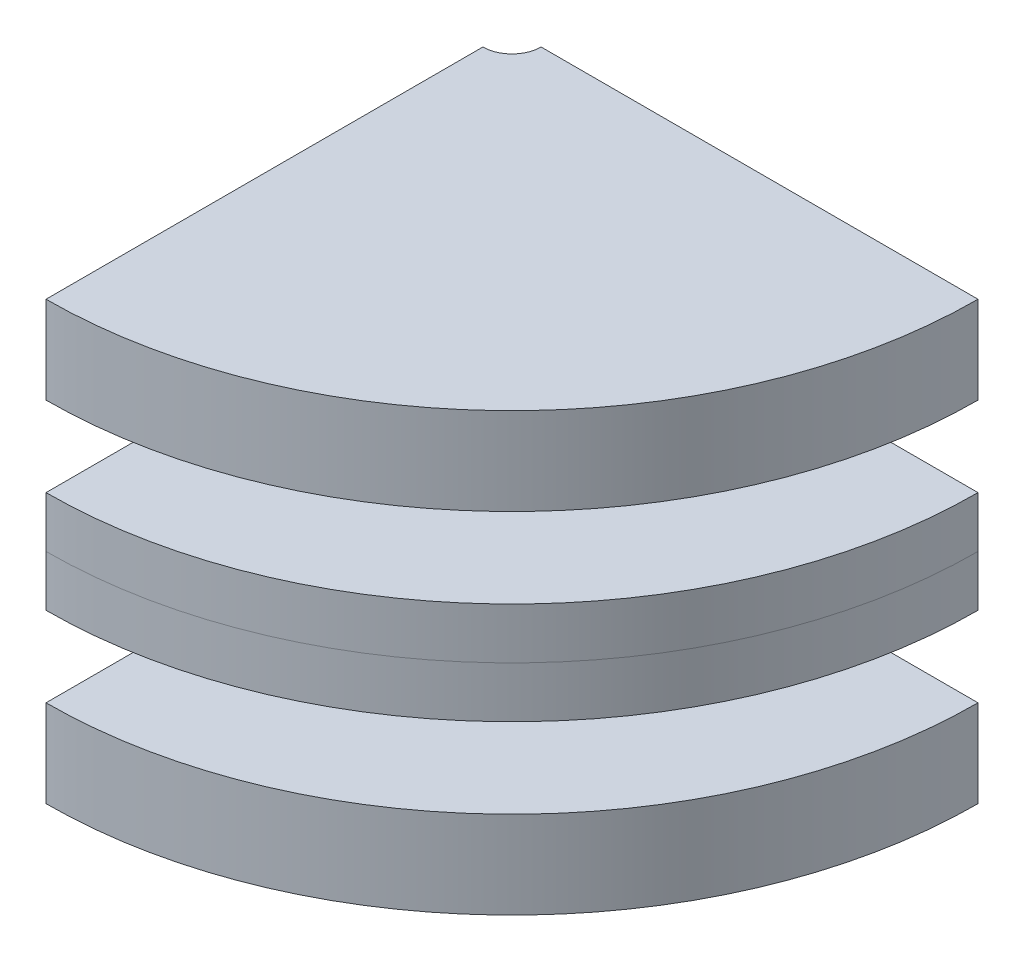
SolidWorks part; units mm, degrees
ref_plane "Front Plane" through (0, 0, 0) normal (0, 0, 1) x (1, 0, 0)
ref_plane "Top Plane" through (0, 0, 0) normal (0, 1, 0) x (1, 0, 0)
ref_plane "Right Plane" through (0, 0, 0) normal (1, 0, 0) x (0, 0, -1)
sketch "Sketch1" plane through (0, 0, 0) normal (0, 1, 0) x (1, 0, 0)
  line L0 (0, 0) -> (0, 15)
  line L1 (1, 16) -> (16, 16)
  line L2 (0, 0) -> (-15.7143, 0) construction
  line L3 (0, 15) -> (-10.8275, 15) construction
  arc A0 (0, 15) -> (1, 16) centre (0, 16) ccw
  arc A1 (0, 0) -> (16, 16) centre (0, 16) ccw
  point P5 (0, 7.5)
  point P6 (8.5, 16)
  point P9 (-10.8275, 15)
  dimension "D1" = 15
  dimension "D2" = 15
  dimension "D3" = 8.5
  dimension "D4" = 8.5
extrude "Boss-Extrude1" add sketch "Sketch1" along normal blind 3
ref_plane "Plane1" through (0, 5.75, 0) normal (0, 1, 0) x (1, 0, 0)
sketch "Sketch2" plane through (0, 5.75, 0) normal (0, 1, 0) x (1, 0, 0)
  line L0 (1, 16) -> (16, 16)
  line L1 (16, 16) -> (1, 16) construction
  line L2 (0, 15) -> (0, 0)
  arc A1 (0, 15) -> (1, 16) centre (0, 16) ccw
  arc A2 (0, 15) -> (1, 16) centre (0, 16) ccw construction
  arc A3 (0, 0) -> (16, 16) centre (0, 16) ccw
  arc A4 (0, 0) -> (16, 16) centre (0, 16) ccw construction
  point P13 (22.3477, 22.5)
extrude "Boss-Extrude2" add sketch "Sketch2" along normal blind 1.75 separate body
mirror "Mirror1" about plane through (0, 7.5, -16) normal (0, 1, 0) of bodies 101 102
